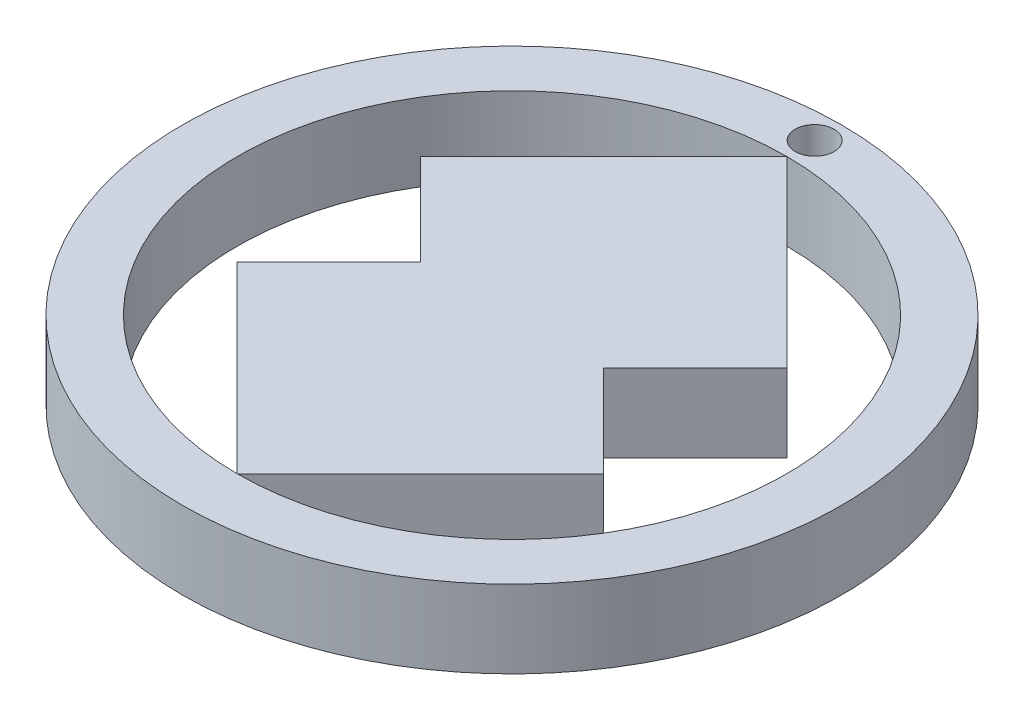
SolidWorks part; units mm, degrees
ref_plane "Front Plane" through (0, 0, 0) normal (0, 0, 1) x (1, 0, 0)
ref_plane "Top Plane" through (0, 0, 0) normal (0, 1, 0) x (1, 0, 0)
ref_plane "Right Plane" through (0, 0, 0) normal (1, 0, 0) x (0, 0, -1)
sketch "Sketch1" plane through (0, 0, 0) normal (0, 1, 0) x (1, 0, 0)
  line L0 (0, 90.0362) -> (0, -90.0362) construction
  line L1 (-76.6844, -76.6844) -> (76.6844, 76.6844) construction
  line L2 (-81.1061, 81.1061) -> (81.1061, -81.1061) construction
  line L3 (-14.1421, 14.1421) -> (0, 28.2843)
  line L4 (-14.1421, 14.1421) -> (-7.0711, 7.0711)
  line L5 (0, 28.2843) -> (14.1421, 14.1421)
  line L7 (-7.0711, 7.0711) -> (-14.1421, 0)
  line L8 (7.0711, 7.0711) -> (14.1421, 0)
  line L9 (-14.1421, 0) -> (0, -14.1421)
  line L10 (14.1421, 0) -> (0, -14.1421)
  line L11 (7.0711, 7.0711) -> (14.1421, 14.1421)
  point P4 (0, 0)
  point P8 (0, 0)
  point P11 (0, 0)
  dimension "D1" = 45
  dimension "D2" = 45
  dimension "D3" = 20
  dimension "D4" = 20
  dimension "D5" = 20
extrude "Boss-Extrude1" add sketch "Sketch1" along normal blind 6
sketch "Sketch2" plane through (0, 6, 0) normal (0, 1, 0) x (1, 0, 0)
  line L0 (0, -14.1421) -> (0, 28.2843) construction
  circle A0 centre (0, 7.0711) radius 21.2132
  circle A1 centre (0, 7.0711) radius 25.44
  point P5 (0, 0)
  point P8 (0, 7.0711)
  point P11 (0, 7.0711)
  dimension "D1" = 42.4264
  dimension "D2" = 50.88
extrude "Boss-Extrude2" add sketch "Sketch2" against normal up to surface (6 mm away) separate body up to face at (0, 0, -7.0711)
sketch "Sketch3" plane through (0, 6, 0) normal (0, 1, 0) x (1, 0, 0)
  circle A0 centre (0, 30.4325) radius 1.5
extrude "Cut-Extrude1" cut sketch "Sketch3" against normal blind 6
